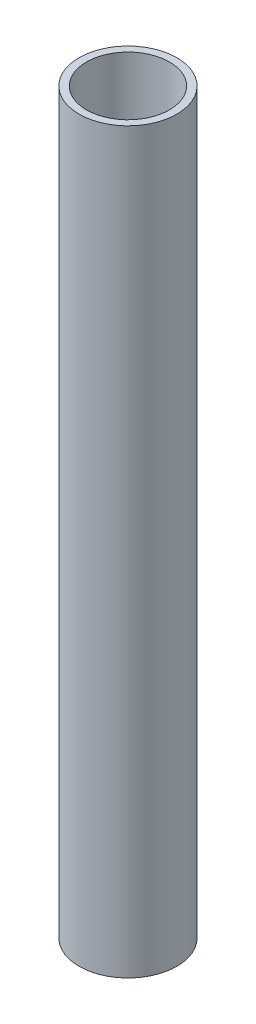
SolidWorks part; units mm, degrees
ref_plane "Front Plane" through (0, 0, 0) normal (0, 0, 1) x (1, 0, 0)
ref_plane "Top Plane" through (0, 0, 0) normal (0, 1, 0) x (1, 0, 0)
ref_plane "Right Plane" through (0, 0, 0) normal (1, 0, 0) x (0, 0, -1)
sketch "Sketch1" plane through (0, 0, 0) normal (0, 1, 0) x (1, 0, 0)
  circle A0 centre (0, 0) radius 7.95
  circle A1 centre (0, 0) radius 6.75
  dimension "D1" = 15.9
  dimension "D2" = 13.5
extrude "Boss-Extrude1" add sketch "Sketch1" along normal blind 120 contours A0 A1
